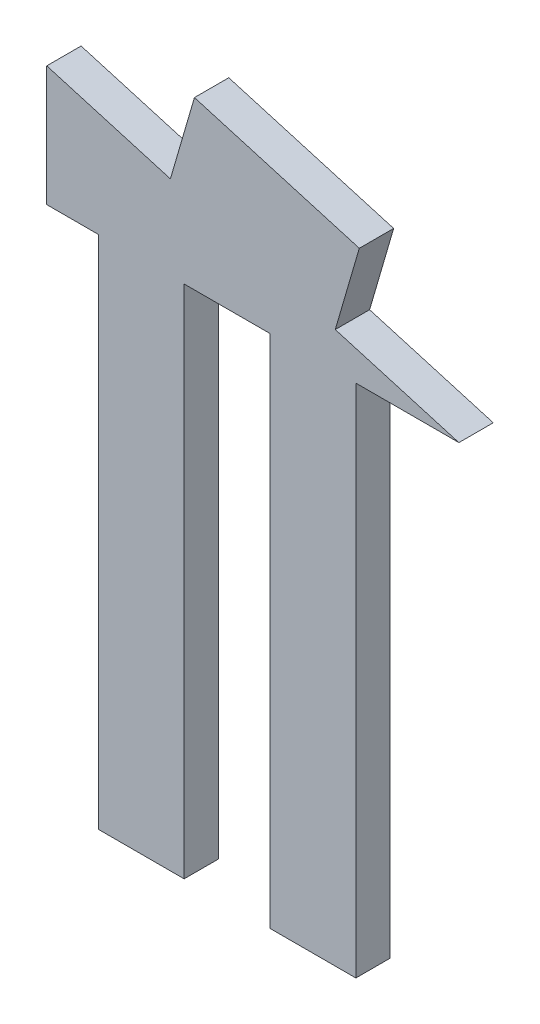
SolidWorks part; units mm, degrees
material "Thornel Mat VMA"
ref_plane "Ön Düzlem" through (0, 0, 0) normal (0, 0, 1) x (1, 0, 0)
ref_plane "Üst Düzlem" through (0, 0, 0) normal (0, 1, 0) x (1, 0, 0)
ref_plane "Sağ Düzlem" through (0, 0, 0) normal (1, 0, 0) x (0, 0, -1)
sketch "Sketch1" plane through (0, 0, 0) normal (0, 0, 1) x (1, 0, 0)
  line L0 (0, 0) -> (24, 0)
  line L1 (24, 0) -> (0, 7)
  line L2 (0, 7) -> (0, 0)
  line L3 (7.2, 4.9) -> (16.8, 2.1)
  line L4 (3, 0) -> (8, 0)
  line L5 (3, 0) -> (3, -100)
  line L6 (3, -100) -> (8, -100)
  line L7 (8, 0) -> (8, -100)
  line L8 (13, 0) -> (18, 0)
  line L9 (13, 0) -> (13, -100)
  line L10 (13, -100) -> (18, -100)
  line L11 (18, 0) -> (18, -100)
  line L12 (7.2, 4.9) -> (8.6, 9.7)
  line L13 (16.8, 2.1) -> (18.2, 6.9)
  line L14 (8.6, 9.7) -> (18.2, 6.9)
  dimension "D1" = 24
  dimension "D2" = 7
  dimension "D3" = 3
  dimension "D4" = 5
  dimension "D5" = 100
  dimension "D6" = 5
  dimension "D7" = 5
  dimension "D8" = 100
  dimension "D9" = 7.5
  dimension "D10" = 10
  dimension "D11" = 5
extrude "Boss-Extrude1" add sketch "Sketch1" along normal blind 2 contours L7 L0 L5 L6 | L11 L0 L9 L10 | L1 L2 L0 | L14 L13 L3 L12
sketch "Sketch2" plane through (0, -100, 0) normal (0, -1, 0) x (1, 0, 0)
  line L1 (3, 0) -> (8, 0)
  line L2 (3, 0) -> (3, 2)
  line L3 (3, 2) -> (8, 2)
  line L4 (8, 0) -> (8, 2)
  line L5 (13, 0) -> (18, 0)
  line L6 (13, 0) -> (13, 2)
  line L7 (13, 2) -> (18, 2)
  line L8 (18, 0) -> (18, 2)
extrude "Cut-Extrude1" cut sketch "Sketch2" against normal blind 50
sketch "Sketch3" plane through (0, -50, 0) normal (0, -1, 0) x (-1, 0, 0)
  line L1 (-3, 0) -> (-8, 0)
  line L2 (-3, 0) -> (-3, -2)
  line L3 (-3, -2) -> (-8, -2)
  line L4 (-8, 0) -> (-8, -2)
  line L5 (-13, 0) -> (-18, 0)
  line L6 (-13, 0) -> (-13, -2)
  line L7 (-13, -2) -> (-18, -2)
  line L8 (-18, 0) -> (-18, -2)
extrude "Cut-Extrude2" cut sketch "Sketch3" against normal blind 20
